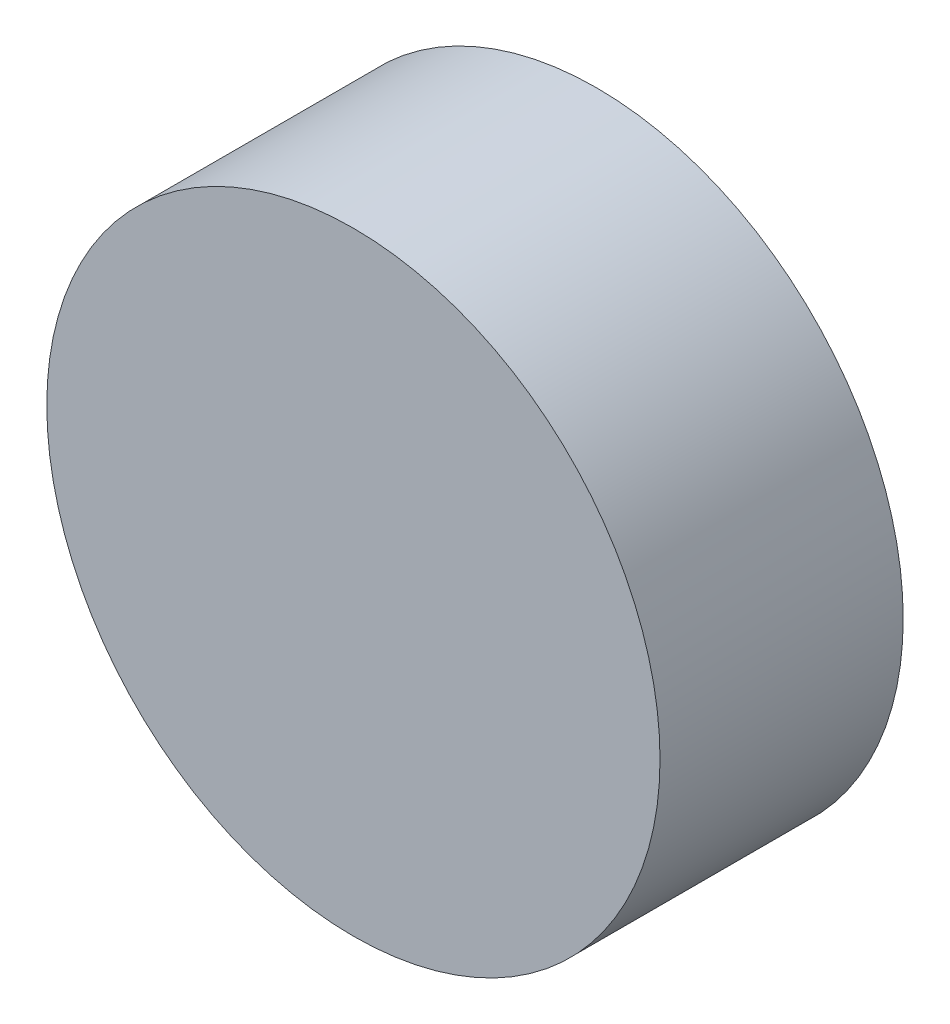
SolidWorks part; units mm, degrees
ref_plane "Front Plane" through (0, 0, 0) normal (0, 0, 1) x (1, 0, 0)
ref_plane "Top Plane" through (0, 0, 0) normal (0, 1, 0) x (1, 0, 0)
ref_plane "Right Plane" through (0, 0, 0) normal (1, 0, 0) x (0, 0, -1)
sketch "Sketch1" plane through (0, 0, 0) normal (0, 0, 1) x (1, 0, 0)
  circle A0 centre (0, 0) radius 5.8
  dimension "D1" = 11.6
extrude "Boss-Extrude1" add sketch "Sketch1" along normal blind 4.6
